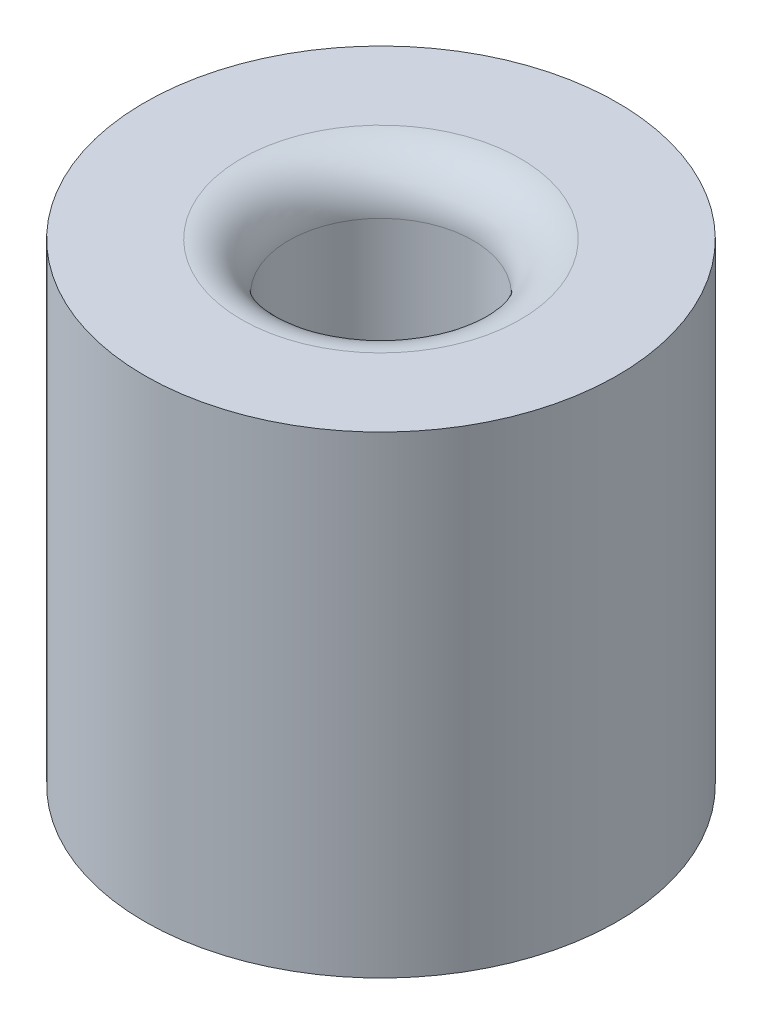
SolidWorks part; units mm, degrees
ref_plane "Спереди" through (0, 0, 0) normal (0, 0, 1) x (1, 0, 0)
ref_plane "Сверху" through (0, 0, 0) normal (0, 1, 0) x (1, 0, 0)
ref_plane "Справа" through (0, 0, 0) normal (1, 0, 0) x (0, 0, -1)
sketch "Эскиз1" plane through (0, 0, 0) normal (0, 1, 0) x (1, 0, 0)
  circle A0 centre (0, 0) radius 5
  dimension "D1" = 10
extrude "Бобышка-Вытянуть1" add sketch "Эскиз1" along normal blind 10
sketch "Эскиз2" plane through (0, 10, 0) normal (0, 1, 0) x (1, 0, 0)
  circle A0 centre (0, 0) radius 1.95
  dimension "D1" = 3.9
extrude "Вырез-Вытянуть1" cut sketch "Эскиз2" against normal blind 8.6 contours A0
fillet "Скругление1" radius 1 1 edges at (0, 10, 1.95)
